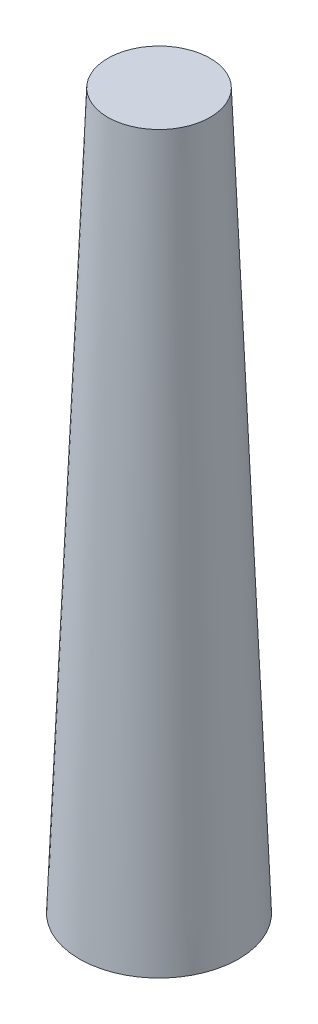
SolidWorks part; units mm, degrees
material "ABS"
ref_plane "Front Plane" through (0, 0, 0) normal (0, 0, 1) x (1, 0, 0)
ref_plane "Top Plane" through (0, 0, 0) normal (0, 1, 0) x (1, 0, 0)
ref_plane "Right Plane" through (0, 0, 0) normal (1, 0, 0) x (0, 0, -1)
sketch "Sketch1" plane through (0, 0, 0) normal (0, 1, 0) x (1, 0, 0)
  circle A0 centre (0, 0) radius 1.8669
  dimension "D1" = 3.7338
ref_plane "Plane1" through (0, 16.764, 0) normal (0, 1, 0) x (1, 0, 0)
sketch "Sketch2" plane through (0, 16.764, 0) normal (0, 1, 0) x (1, 0, 0)
  circle A0 centre (0, 0) radius 1.2001
  dimension "D1" = 2.4003
loft "Loft1" add profiles "Sketch2", "Sketch1"
